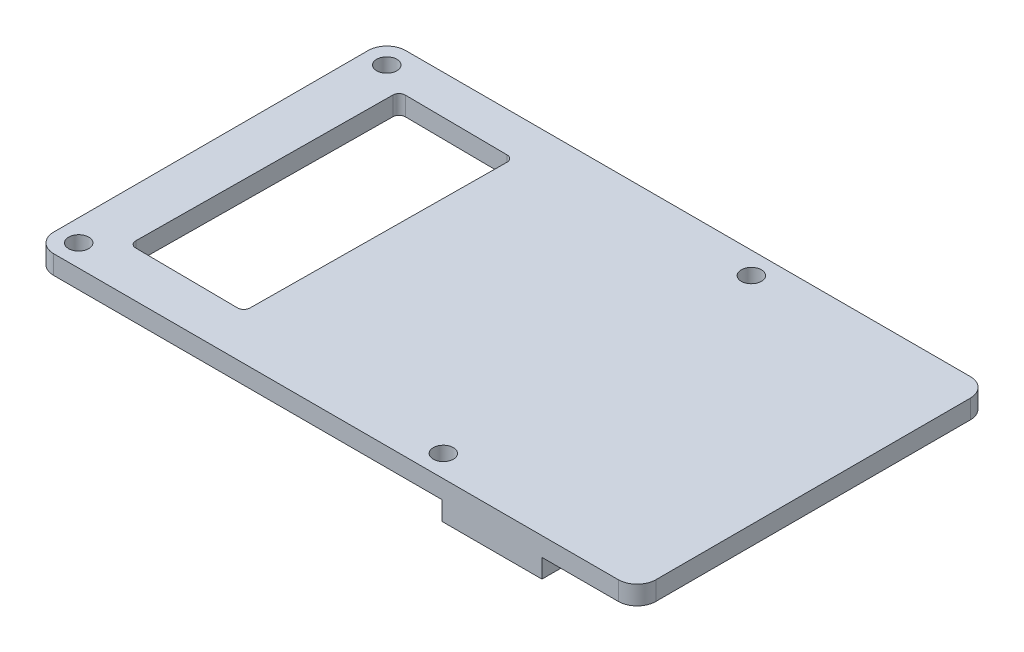
SolidWorks part; units mm, degrees
material "7075-T6 (SN)"
ref_plane "前视基准面" through (0, 0, 0) normal (0, 0, 1) x (1, 0, 0)
ref_plane "上视基准面" through (0, 0, 0) normal (0, 1, 0) x (1, 0, 0)
ref_plane "右视基准面" through (0, 0, 0) normal (1, 0, 0) x (0, 0, -1)
other "Configuration Table"
sketch "草图1" plane through (0, 0, 0) normal (0, 1, 0) x (1, 0, 0)
  line L8 (-70.9034, 18.2303) -> (-54.5645, 18.0823)
  line L9 (-53.5736, 17.0733) -> (-53.9406, -23.4455)
  line L10 (-54.9496, -24.4364) -> (-71.2885, -24.2884)
  line L11 (-71.9124, 17.2394) -> (-72.2794, -23.2794)
  line L12 (-80.009, 21.4027) -> (-80.009, -28.6044)
  line L13 (-77.0217, -31.5917) -> (12.7873, -31.5917)
  line L14 (15.7746, -28.6044) -> (15.7746, 21.4027)
  line L15 (12.7873, 24.39) -> (-77.0217, 24.39)
  line L16 (-80.009, 21.4027) -> (-80.009, -28.6044)
  line L17 (-77.0217, -31.5917) -> (12.7873, -31.5917)
  line L18 (15.7746, -28.6044) -> (15.7746, 21.4027)
  line L19 (12.7873, 24.39) -> (-77.0217, 24.39)
  circle A4 centre (-76.5285, 20.8867) radius 1.6
  circle A5 centre (-18.5286, 20.8866) radius 1.6
  circle A6 centre (-18.5283, -28.1137) radius 1.6
  circle A7 centre (-76.5283, -28.1135) radius 1.6
  arc A8 (-80.009, -28.6044) -> (-77.0217, -31.5917) centre (-77.0217, -28.6044) ccw
  arc A9 (12.7873, -31.5917) -> (15.7746, -28.6044) centre (12.7873, -28.6044) ccw
  arc A10 (15.7746, 21.4027) -> (12.7873, 24.39) centre (12.7873, 21.4027) ccw
  arc A11 (-77.0217, 24.39) -> (-80.009, 21.4027) centre (-77.0217, 21.4027) ccw
  arc A12 (-80.009, -28.6044) -> (-77.0217, -31.5917) centre (-77.0217, -28.6044) ccw
  arc A13 (12.7873, -31.5917) -> (15.7746, -28.6044) centre (12.7873, -28.6044) ccw
  arc A14 (15.7746, 21.4027) -> (12.7873, 24.39) centre (12.7873, 21.4027) ccw
  arc A15 (-77.0217, 24.39) -> (-80.009, 21.4027) centre (-77.0217, 21.4027) ccw
  arc A16 (-71.2885, -24.2884) -> (-72.2794, -23.2794) centre (-71.2794, -23.2885) cw
  arc A17 (-53.5736, 17.0733) -> (-54.5645, 18.0823) centre (-54.5735, 17.0823) ccw
  arc A18 (-70.9034, 18.2303) -> (-71.9124, 17.2394) centre (-70.9125, 17.2303) ccw
  arc A19 (-53.9406, -23.4455) -> (-54.9496, -24.4364) centre (-54.9405, -23.4364) cw
  dimension "D2" = 3.2
  dimension "D3" = 3.2
  dimension "D4" = 3.2
  dimension "D5" = 3.2
  dimension "D6" = 1
  dimension "D7" = 1
  dimension "D1" = 0
extrude "凸台-拉伸1" add sketch "草图1" along normal blind 3
sketch "草图3" plane through (0, 0, 0) normal (0, -1, 0) x (1, 0, 0)
  line L0 (-77.0217, 31.5917) -> (12.7873, 31.5917) construction
  line L1 (-15.2271, 31.5917) -> (0.6393, 31.5917)
  line L2 (-15.2271, 31.5917) -> (-15.2271, -24.39)
  line L3 (-15.2271, -24.39) -> (0.6393, -24.39)
  line L4 (0.6393, 31.5917) -> (0.6393, -24.39)
  line L5 (12.7873, -24.39) -> (-77.0217, -24.39) construction
  line L7 (-36.8658, -15.5141) -> (-24.8441, -15.5141)
  line L8 (-36.8658, -15.5141) -> (-36.8658, 23.3522)
  line L9 (-36.8658, 23.3522) -> (-24.8441, 23.3522)
  line L10 (-24.8441, -15.5141) -> (-24.8441, 23.3522)
extrude "凸台-拉伸3" add sketch "草图3" along normal blind 3
